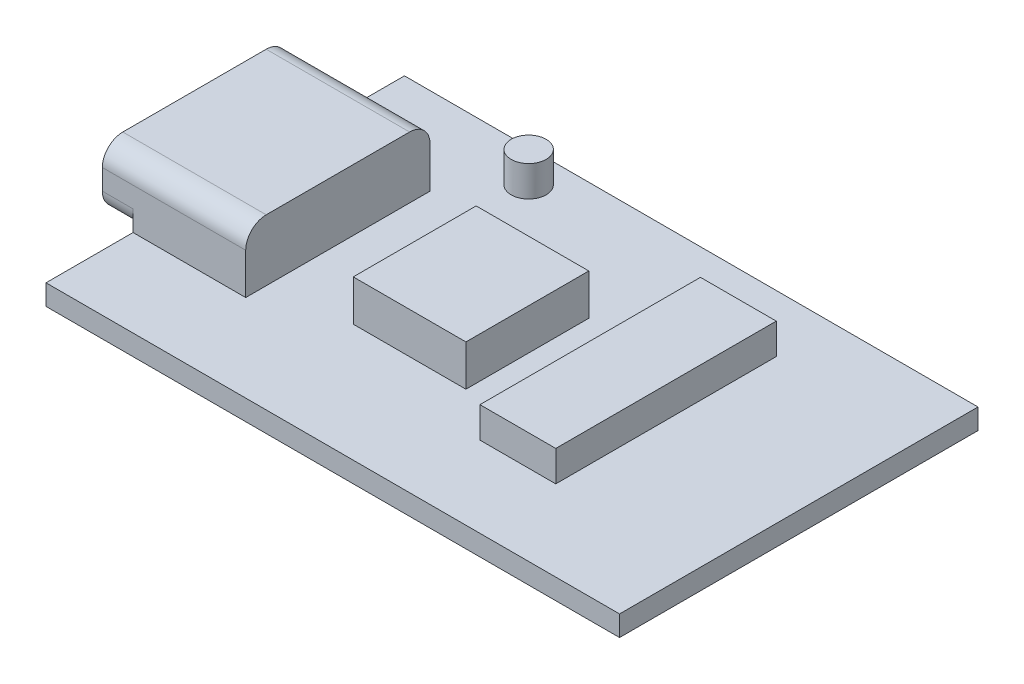
SolidWorks part; units mm, degrees
ref_plane "Front Plane" through (0, 0, 0) normal (0, 0, 1) x (1, 0, 0)
ref_plane "Top Plane" through (0, 0, 0) normal (0, 1, 0) x (1, 0, 0)
ref_plane "Right Plane" through (0, 0, 0) normal (1, 0, 0) x (0, 0, -1)
sketch "Sketch1" plane through (0, 0, 0) normal (0, 1, 0) x (1, 0, 0)
  line L1 (14, 8.75) -> (-14, 8.75)
  line L2 (14, 8.75) -> (14, -8.75)
  line L3 (14, -8.75) -> (-14, -8.75)
  line L4 (-14, 8.75) -> (-14, -8.75)
  line L5 (14, 8.75) -> (-14, -8.75) construction
  line L6 (14, -8.75) -> (-14, 8.75) construction
  point P0 (0, 0)
  dimension "D1" = 28
  dimension "D2" = 17.5
extrude "Boss-Extrude1" add sketch "Sketch1" along normal blind 1
sketch "Sketch2" plane through (0, 1, 0) normal (0, 1, 0) x (1, 0, 0)
  line L0 (-14, 8.75) -> (-14, -8.75) construction
  line L1 (-15.5, 4.5) -> (-8.5, 4.5)
  line L2 (-15.5, 4.5) -> (-15.5, -4.5)
  line L3 (-15.5, -4.5) -> (-8.5, -4.5)
  line L4 (-8.5, 4.5) -> (-8.5, -4.5)
  point P4 (-8.5, 0)
  dimension "D1" = 7
  dimension "D2" = 9
  dimension "D3" = 1.5
extrude "Boss-Extrude2" add sketch "Sketch2" along normal blind 3
fillet "Fillet1" radius 1 4 edges at (-14.75, 1, -4.5) (-14.75, 1, 4.5) (-12, 4, -4.5) (-12, 4, 4.5)
sketch "Sketch3" plane through (0, 1, 0) normal (0, 1, 0) x (1, 0, 0)
  line L0 (14, -8.75) -> (14, 8.75) construction
  line L1 (0.75, -3) -> (-4.75, -3)
  line L2 (0.75, -3) -> (0.75, 3)
  line L3 (0.75, 3) -> (-4.75, 3)
  line L4 (-4.75, -3) -> (-4.75, 3)
  line L5 (0.75, -3) -> (-4.75, 3) construction
  line L6 (0.75, 3) -> (-4.75, -3) construction
  point P0 (-2, 0)
  dimension "D1" = 5.5
  dimension "D2" = 6
  dimension "D3" = 16
extrude "Boss-Extrude3" add sketch "Sketch3" along normal blind 2
sketch "Sketch4" plane through (0, 1, 0) normal (0, 1, 0) x (1, 0, 0)
  line L1 (3.2447, 5.9554) -> (6.9458, 5.9554)
  line L2 (3.2447, 5.9554) -> (3.2447, -4.8098)
  line L3 (3.2447, -4.8098) -> (6.9458, -4.8098)
  line L4 (6.9458, 5.9554) -> (6.9458, -4.8098)
  circle A0 centre (-6.3603, 7.1744) radius 0.8526
  point P6 (3.5385, -3.9727)
  point P7 (6.9458, 5.9554)
  point P8 (3.2447, -4.8098)
  point P9 (-5.6994, 6.8219)
  point P10 (-6.3603, 7.1744)
extrude "Boss-Extrude5" add sketch "Sketch4" along normal blind 1.5
